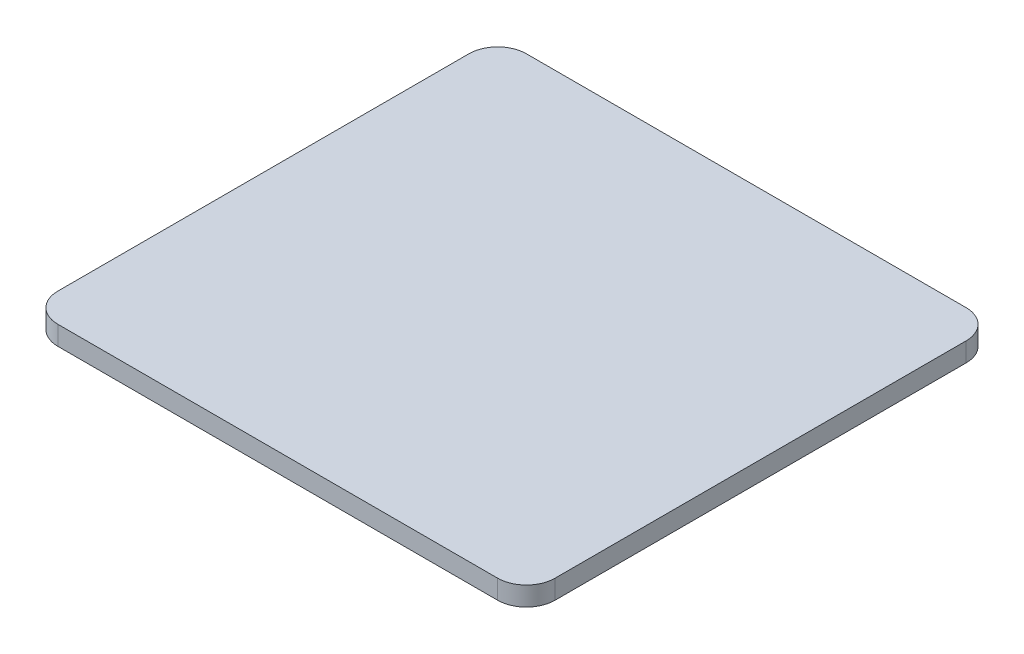
SolidWorks part; units mm, degrees
ref_plane "Front Plane" through (0, 0, 0) normal (0, 0, 1) x (1, 0, 0)
ref_plane "Top Plane" through (0, 0, 0) normal (0, 1, 0) x (1, 0, 0)
ref_plane "Right Plane" through (0, 0, 0) normal (1, 0, 0) x (0, 0, -1)
other "Configuration Table"
sketch "Sketch3" plane through (0, 0, 0) normal (0, 1, 0) x (1, 0, 0)
  line L0 (-91.0159, 50.8359) -> (-91.0159, 1.8359)
  line L1 (-91.0159, 50.8359) -> (-39.0159, 50.8359)
  line L3 (-91.0159, 1.8359) -> (-39.0159, 1.8359)
  line L5 (-39.0159, 50.8359) -> (-39.0159, 1.8359)
  dimension "D1" = 52
  dimension "D2" = 49
extrude "Boss-Extrude3" add sketch "Sketch3" along normal blind 2
sketch "Sketch5" plane through (0, 0, 0) normal (0, -1, 0) x (1, 0, 0)
  line L0 (-91.0159, -50.8359) -> (-91.0159, -1.8359) construction
  circle A0 centre (-62.0159, -26.3359) radius 3.5
  circle A1 centre (-62.0159, -26.3359) radius 2.5
  dimension "D1" = 5
  dimension "D2" = 7
  dimension "D3" = 29
extrude "Boss-Extrude5" add sketch "Sketch5" along normal blind 3
fillet "Fillet1" radius 3 4 edges at (-91.0159, 1, -50.8359) (-91.0159, 1, -1.8359) (-39.0159, 1, -50.8359) (-39.0159, 1, -1.8359)
